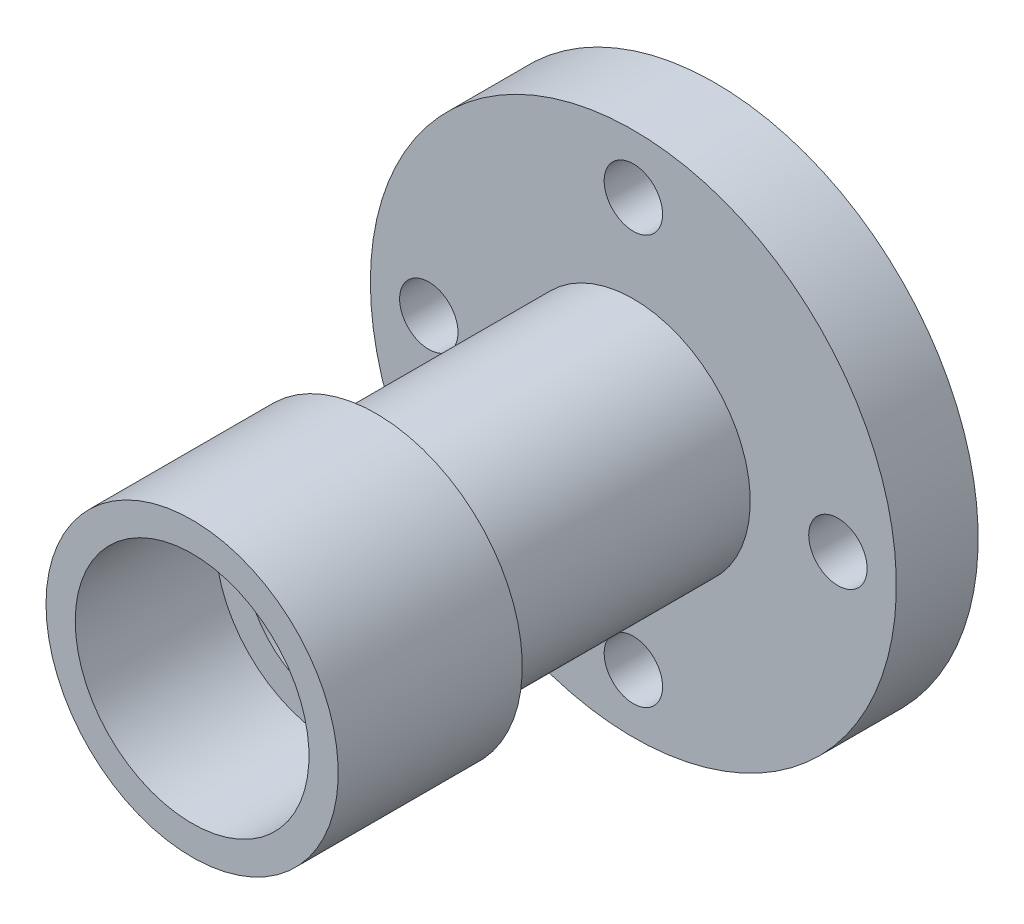
SolidWorks part; units mm, degrees
ref_plane "Front Plane" through (0, 0, 0) normal (0, 0, 1) x (1, 0, 0)
ref_plane "Top Plane" through (0, 0, 0) normal (0, 1, 0) x (1, 0, 0)
ref_plane "Right Plane" through (0, 0, 0) normal (1, 0, 0) x (0, 0, -1)
sketch "Sketch1" plane through (0, 0, 0) normal (1, 0, 0) x (0, 0, -1)
  line L0 (0, 25) -> (0, 20)
  line L1 (0, 20) -> (24, 20)
  line L2 (24, 20) -> (24, 15)
  line L3 (24, 15) -> (33.5, 15)
  line L4 (33.5, 15) -> (33.5, 17)
  line L5 (33.5, 17) -> (35.5, 17)
  line L6 (35.5, 17) -> (35.5, 15)
  line L7 (35.5, 15) -> (48, 15)
  line L8 (48, 15) -> (48, 18.5)
  line L9 (48, 18.5) -> (51.5, 18.5)
  line L10 (51.5, 18.5) -> (51.5, 15)
  line L11 (51.5, 15) -> (63.5, 15)
  line L12 (63.5, 15) -> (63.5, 17)
  line L13 (63.5, 17) -> (65.5, 17)
  line L14 (65.5, 17) -> (65.5, 15)
  line L15 (65.5, 15) -> (86, 15)
  line L16 (86, 15) -> (89.5, 18.5)
  line L17 (89.5, 18.5) -> (89.5, 23)
  line L18 (89.5, 23) -> (83.5, 23)
  line L19 (83.5, 23) -> (83.5, 27)
  line L20 (83.5, 27) -> (89.5, 27)
  line L21 (89.5, 27) -> (89.5, 45)
  line L22 (89.5, 45) -> (75.5, 45)
  line L23 (75.5, 45) -> (75.5, 20)
  line L24 (75.5, 20) -> (31.5, 20)
  line L25 (31.5, 20) -> (31.5, 25)
  line L26 (31.5, 25) -> (0, 25)
  line L27 (114.1366, 0) -> (0, 0) construction
  point P28 (63.5, 16)
  dimension "D1" = 89.5
  dimension "D2" = 3.5
  dimension "D3" = 2
  dimension "D4" = 3.5
  dimension "D5" = 3.5
  dimension "D6" = 4
  dimension "D7" = 6
  dimension "D8" = 24
  dimension "D9" = 38
  dimension "D10" = 54
  dimension "D11" = 31.5
  dimension "D12" = 23
  dimension "D13" = 24
  dimension "D14" = 5
  dimension "D15" = 5
  dimension "D16" = 25
  dimension "D17" = 14
  dimension "D18" = 45
revolve "Revolve1" add sketch "Sketch1" angle 360 about L27
sketch "Sketch2" plane through (0, 0, -89.5) normal (0, 0, -1) x (-1, 0, 0)
  circle A1 centre (0, 35) radius 5
  circle A2 centre (35, 0) radius 5
  circle A3 centre (0, -35) radius 5
  circle A4 centre (-35, 0) radius 5
  circle A5 centre (0, 0) radius 35 construction
  point P1 (0, 0)
  point P12 (-35, 0)
  point P13 (0, 0)
  point P14 (0, -35)
  point P15 (0, 0)
  point P16 (0, 0)
  point P17 (0, 0)
  point P18 (0, 0)
  point P19 (0, 0)
  point P20 (0, 0)
  point P21 (35, 0)
  dimension "D2" = 10
  dimension "D3" = 35
extrude "Cut-Extrude1" cut sketch "Sketch2" against normal through all
